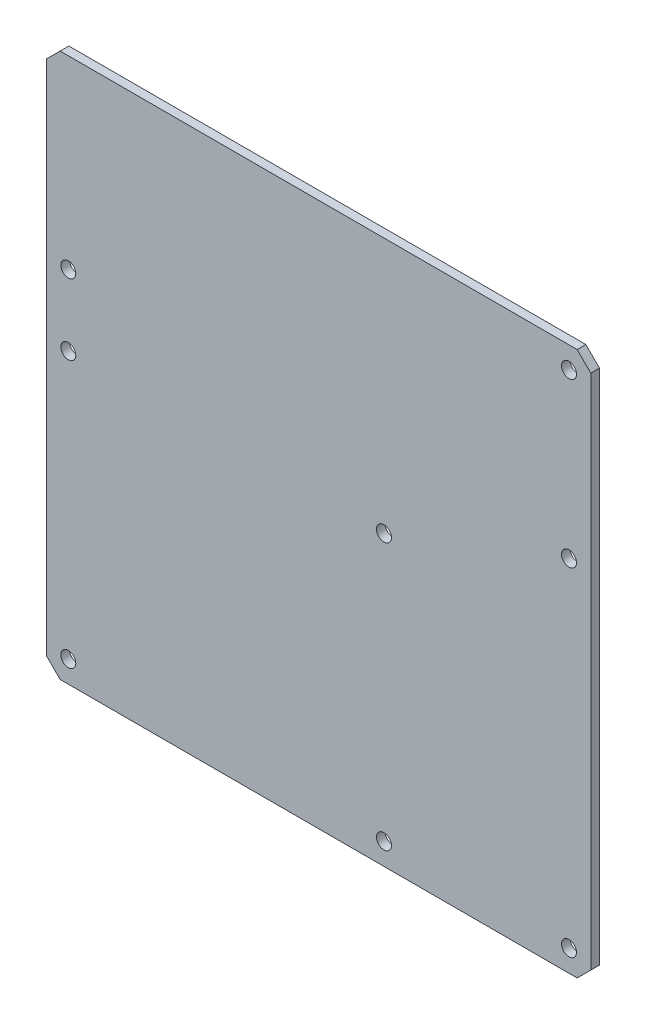
SolidWorks part; units mm, degrees
ref_plane "Plan de face" through (0, 0, 0) normal (0, 0, 1) x (1, 0, 0)
ref_plane "Plan de dessus" through (0, 0, 0) normal (0, 1, 0) x (1, 0, 0)
ref_plane "Plan de droite" through (0, 0, 0) normal (1, 0, 0) x (0, 0, -1)
sketch "Esquisse1" plane through (0, 0, 0) normal (0, 0, 1) x (1, 0, 0)
  line L0 (-55.8676, -51.7778) -> (-58.3676, -49.2778)
  line L1 (-58.3676, 48.2222) -> (41.6324, 48.2222)
  line L2 (-58.3676, 48.2222) -> (-58.3676, -51.7778)
  line L3 (-58.3676, -51.7778) -> (41.6324, -51.7778)
  line L4 (41.6324, 48.2222) -> (41.6324, -51.7778)
  line L5 (-58.3676, 45.7222) -> (-55.8676, 48.2222)
  line L6 (39.1324, -51.7778) -> (41.6324, -49.2778)
  line L7 (41.6324, 45.7222) -> (39.1324, 48.2222)
  circle A0 centre (-54.3676, -47.7778) radius 1.375
  circle A1 centre (3.6324, -47.7778) radius 1.375
  circle A2 centre (3.6324, 1.2222) radius 1.375
  circle A3 centre (-54.3676, 1.2222) radius 1.375
  circle A4 centre (37.6324, -47.7778) radius 1.375
  circle A5 centre (-54.3676, 14.2222) radius 1.375
  circle A6 centre (37.6324, 14.2222) radius 1.375
  circle A7 centre (37.6324, 44.2222) radius 1.375
  dimension "D7" = 2.75
  dimension "D8" = 2.75
  dimension "D9" = 4
  dimension "D10" = 2.75
  dimension "D11" = 2.75
  dimension "D12" = 2.75
  dimension "D13" = 2.75
  dimension "D14" = 2.75
  dimension "D15" = 4
  dimension "D6" = 2.75
  dimension "D1" = 100
  dimension "D2" = 100
  dimension "D3" = 49
  dimension "D4" = 62
  dimension "D5" = 58
  dimension "D16" = 4
  dimension "D17" = 4
  dimension "D18" = 4
  dimension "D19" = 4
  dimension "D20" = 49
  dimension "D21" = 58
  dimension "D22" = 92
  dimension "D23" = 62
  dimension "D24" = 4
  dimension "D25" = 92
  dimension "D26" = 4
  dimension "D27" = 2.5
  dimension "D28" = 2.5
  dimension "D29" = 2.5
  dimension "D30" = 2.5
  dimension "D31" = 2.5
  dimension "D32" = 2.5
  dimension "D33" = 2.5
  dimension "D34" = 2.5
extrude "Boss.-Extru.1" add sketch "Esquisse1" along normal blind 1.6 contours L4 L7 L1 L5 L2 L0 L3 L6 A7 A6 A5 A4 A3 A2 A1 A0
